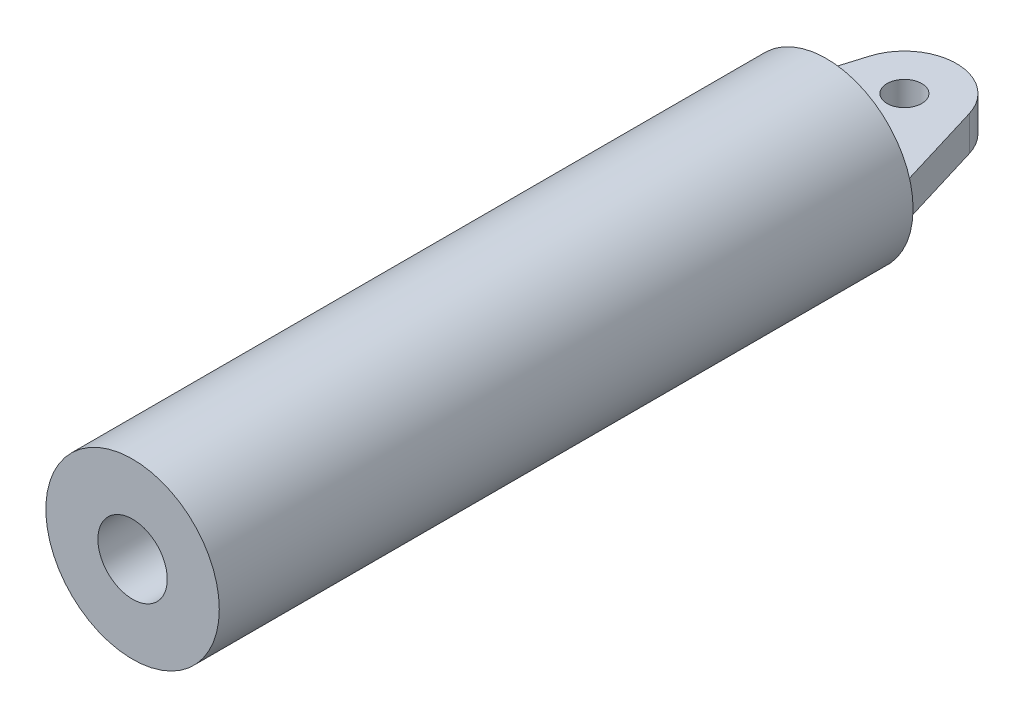
SolidWorks part; units mm, degrees
ref_plane "Front Plane" through (0, 0, 0) normal (0, 0, 1) x (1, 0, 0)
ref_plane "Top Plane" through (0, 0, 0) normal (0, 1, 0) x (1, 0, 0)
ref_plane "Right Plane" through (0, 0, 0) normal (1, 0, 0) x (0, 0, -1)
sketch "Sketch1" plane through (0, 0, 0) normal (0, 0, 1) x (1, 0, 0)
  circle A0 centre (0, 0) radius 50
  dimension "D1" = 100
extrude "Boss-Extrude1" add sketch "Sketch1" along normal blind 400
shell "Shell1" thickness 30
sketch "Sketch2" plane through (0, 0, 0) normal (0, 1, 0) x (1, 0, 0)
  line L0 (-45, 0) -> (-28.7083, 53.7083)
  line L1 (50, 0) -> (-50, 0) construction
  line L2 (0, 0) -> (0, 231.1371) construction
  line L3 (28.7083, 53.7083) -> (45, 0)
  line L4 (-45, 0) -> (45, 0)
  circle A0 centre (0, 45) radius 10
  arc A1 (-28.7083, 53.7083) -> (28.7083, 53.7083) centre (0, 45) cw
  dimension "D1" = 20
  dimension "D2" = 30
  dimension "D3" = 45
  dimension "D4" = 45
extrude "Boss-Extrude2" add sketch "Sketch2" along normal mid plane 20 contours L4 L2 A0 A1 L0 | L2 L4 L3 A1 A0
